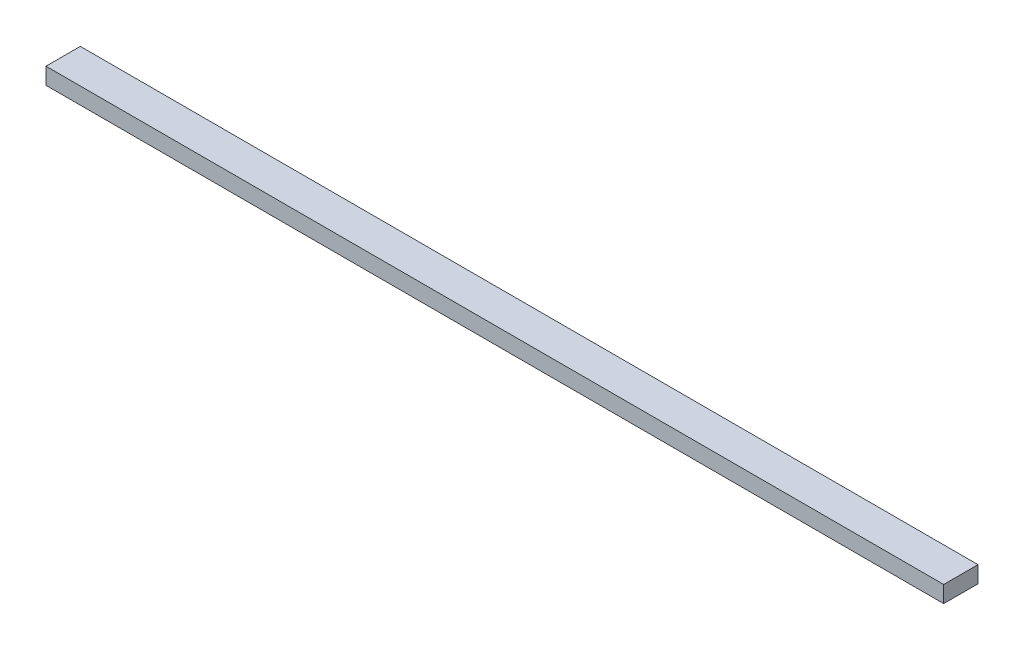
SolidWorks part; units mm, degrees
ref_plane "Front Plane" through (0, 0, 0) normal (0, 0, 1) x (1, 0, 0)
ref_plane "Top Plane" through (0, 0, 0) normal (0, 1, 0) x (1, 0, 0)
ref_plane "Right Plane" through (0, 0, 0) normal (1, 0, 0) x (0, 0, -1)
other "Graphic1"
other "Graphic (Closed) -1"
sketch "Sketch1" plane through (0, 0, 0) normal (1, 0, 0) x (0, 0, -1)
  line L1 (-15.7358, 90.5986) -> (-9.8868, 90.5986)
  line L2 (-15.7358, 90.5986) -> (-15.7358, 87.7679)
  line L3 (-15.7358, 87.7679) -> (-9.8868, 87.7679)
  line L4 (-9.8868, 90.5986) -> (-9.8868, 87.7679)
  point P4 (-15.7358, 87.7679)
  point P5 (-9.8868, 90.5986)
extrude "Boss-Extrude1" add sketch "Sketch1" along normal blind 153
